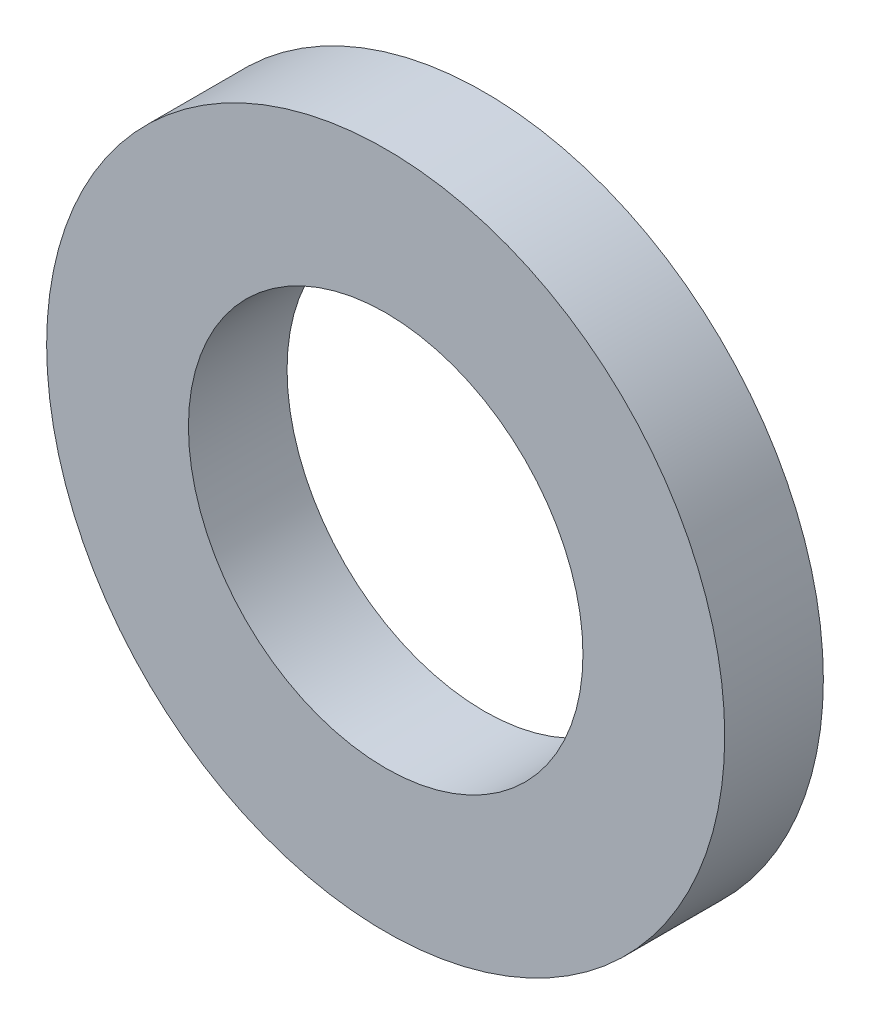
SolidWorks part; units mm, degrees
material "PET"
ref_plane "Front Plane" through (0, 0, 0) normal (1, 0, 0) x (0, 1, 0)
ref_plane "Top Plane" through (0, 0, 0) normal (0, 0, 1) x (0, 1, 0)
ref_plane "Right Plane" through (0, 0, 0) normal (0, 1, 0) x (-1, 0, 0)
sketch "Sketch1" plane through (0, 0, 0) normal (0, 0, 1) x (0, 1, 0)
  circle A0 centre (0, 0) radius 1.6
  circle A1 centre (0, 0) radius 2.75
  dimension "D1" = 3.2
  dimension "D2" = 5.5
extrude "Boss-Extrude1" add sketch "Sketch1" along normal blind 0.8
